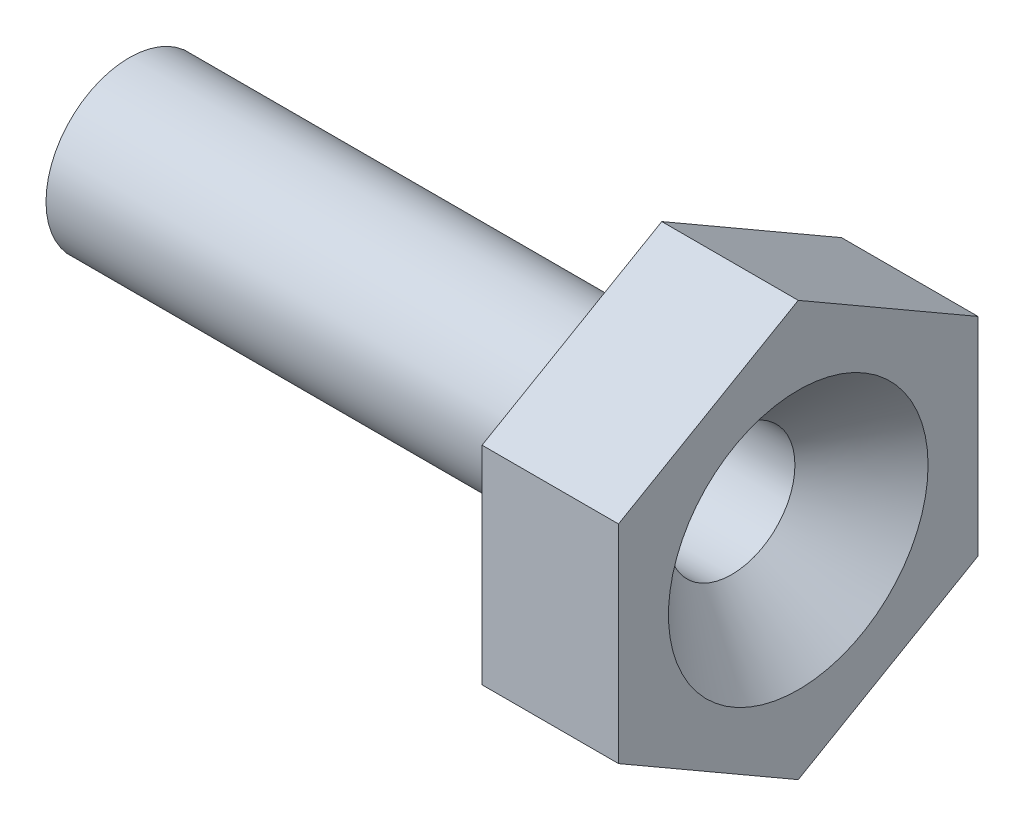
SolidWorks part; units mm, degrees
ref_plane "Front Plane" through (0, 0, 0) normal (0, 0, 1) x (1, 0, 0)
ref_plane "Top Plane" through (0, 0, 0) normal (0, 1, 0) x (1, 0, 0)
ref_plane "Right Plane" through (0, 0, 0) normal (1, 0, 0) x (0, 0, -1)
sketch "Sketch1" plane through (0, 0, 0) normal (1, 0, 0) x (0, 0, -1)
  line L0 (-1000, 0) -> (49000, 0) construction
  line L1 (0, -3.1177) -> (2.7, -1.5588)
  line L2 (2.7, -1.5588) -> (2.7, 1.5588)
  line L3 (2.7, 1.5588) -> (0, 3.1177)
  line L4 (0, 3.1177) -> (-2.7, 1.5588)
  line L5 (-2.7, 1.5588) -> (-2.7, -1.5588)
  line L6 (-2.7, -1.5588) -> (0, -3.1177)
  line L7 (0, -1000) -> (0, 49000) construction
  circle A0 centre (0, 0) radius 2.7 construction
  dimension "D1" = 5.4
extrude "Boss-Extrude1" add sketch "Sketch1" along normal blind 2.05
sketch "Sketch2" plane through (0, 0, 0) normal (-1, 0, 0) x (0, 0, 1)
  circle A0 centre (0, 0) radius 1.25
  dimension "D1" = 2.5
extrude "Boss-Extrude2" add sketch "Sketch2" along normal blind 8
sketch "Sketch3" plane through (-8, 0, 0) normal (-1, 0, 0) x (0, 0, 1)
  circle A0 centre (0, 0) radius 0.95
  dimension "D1" = 1.9
extrude "Cut-Extrude1" cut sketch "Sketch3" against normal through all
chamfer "Chamfer1" distance 1 angle 45 1 edges at (2.05, 0, 0.95)
sketch "Sketch4" plane through (-8, 0, 0) normal (-1, 0, 0) x (0, 0, 1)
  circle A0 centre (0, 0) radius 1.625 construction
  dimension "D1" = 3.25
